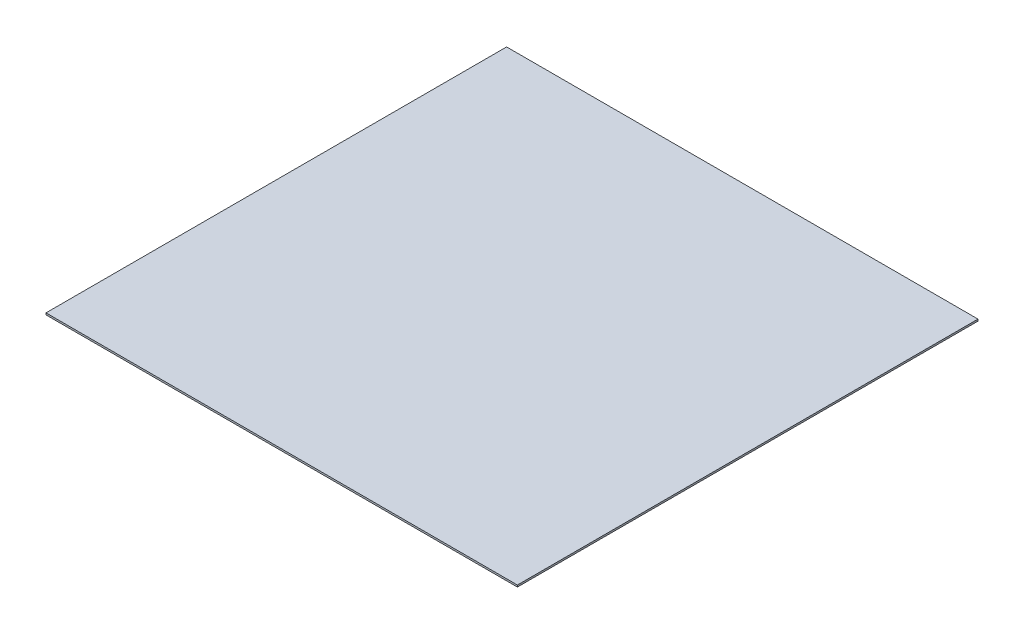
SolidWorks part; units mm, degrees
ref_plane "Front Plane" through (0, 0, 0) normal (0, 0, 1) x (1, 0, 0)
ref_plane "Top Plane" through (0, 0, 0) normal (0, 1, 0) x (1, 0, 0)
ref_plane "Right Plane" through (0, 0, 0) normal (1, 0, 0) x (0, 0, -1)
sketch "Sketch1" plane through (0, 0, 0) normal (0, 1, 0) x (1, 0, 0)
  line L1 (0, 0) -> (831.85, 0)
  line L2 (0, 0) -> (0, 812.8)
  line L3 (0, 812.8) -> (831.85, 812.8)
  line L4 (831.85, 0) -> (831.85, 812.8)
  dimension "D1" = 812.8
  dimension "D2" = 831.85
extrude "Boss-Extrude1" add sketch "Sketch1" along normal blind 3.175
